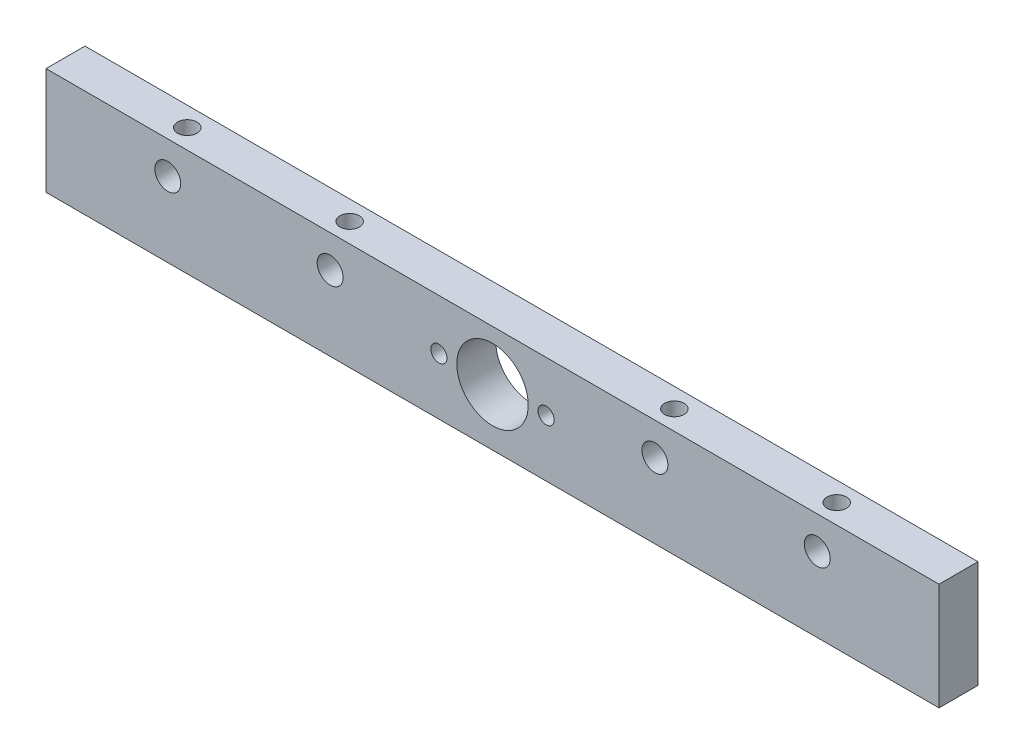
SolidWorks part; units mm, degrees
other "DetailItem1"
other "DetailItem2"
material "Beech"
ref_plane "Front Plane" through (0, 0, 0) normal (0, 0, 1) x (1, 0, 0)
ref_plane "Top Plane" through (0, 0, 0) normal (0, 1, 0) x (1, 0, 0)
ref_plane "Right Plane" through (0, 0, 0) normal (1, 0, 0) x (0, 0, -1)
sketch "Sketch1" plane through (0, 0, 0) normal (0, 0, 1) x (1, 0, 0)
  line L1 (-137.5, -16.5) -> (137.5, -16.5)
  line L2 (-137.5, -16.5) -> (-137.5, 16.5)
  line L3 (-137.5, 16.5) -> (137.5, 16.5)
  line L4 (137.5, -16.5) -> (137.5, 16.5)
  line L5 (-137.5, -16.5) -> (137.5, 16.5) construction
  line L6 (-137.5, 16.5) -> (137.5, -16.5) construction
  point P0 (0, 0)
  dimension "D1" = 275
  dimension "D2" = 33
extrude "Boss-Extrude1" add sketch "Sketch1" along normal blind 12
sketch "Sketch2" plane through (0, 0, 12) normal (0, 0, 1) x (1, 0, 0)
  line L0 (137.5, 16.5) -> (-137.5, 16.5) construction
  line L1 (-16.5, 1) -> (20.0379, 1) construction
  circle A0 centre (0, 1) radius 11
  circle A1 centre (-16.5, 1) radius 2.5
  circle A2 centre (16.5, 1) radius 2.5
  point P2 (0, 16.5)
  dimension "D1" = 15.5
  dimension "D2" = 22
  dimension "D3" = 5
  dimension "D4" = 5
  dimension "D5" = 33
  dimension "D6" = 16.5
extrude "Cut-Extrude1" cut sketch "Sketch2" against normal up to next
sketch "Sketch3" plane through (0, 0, 12) normal (0, 0, 1) x (1, 0, 0)
  line L0 (-143.8537, 6.5) -> (150.4691, 6.5) construction
  line L1 (137.5, 16.5) -> (-137.5, 16.5) construction
  circle A0 centre (-100, 6.5) radius 4
  circle A1 centre (-50, 6.5) radius 4
  circle A2 centre (50, 6.5) radius 4
  circle A3 centre (100, 6.5) radius 4
  circle A4 centre (0, 1) radius 11 construction
  dimension "D2" = 8
  dimension "D3" = 8
  dimension "D4" = 8
  dimension "D5" = 8
  dimension "D6" = 50
  dimension "D7" = 50
  dimension "D8" = 50
  dimension "D9" = 50
  dimension "D1" = 10
extrude "Cut-Extrude2" cut sketch "Sketch3" against normal up to next
sketch "Sketch4" plane through (0, 16.5, 0) normal (0, 1, 0) x (1, 0, 0)
  line L0 (-137.8368, -6) -> (139.4923, -6) construction
  line L2 (0, 6.6834) -> (0, -14.574) construction
  circle A0 centre (-100, -6) radius 3
  circle A1 centre (-50, -6) radius 3
  circle A2 centre (50, -6) radius 3
  circle A3 centre (100, -6) radius 3
  dimension "D1" = 6
  dimension "D2" = 6
  dimension "D3" = 6
  dimension "D4" = 6
  dimension "D5" = 50
  dimension "D6" = 50
  dimension "D8" = 50
  dimension "D7" = 50
extrude "Cut-Extrude3" cut sketch "Sketch4" against normal up to next
